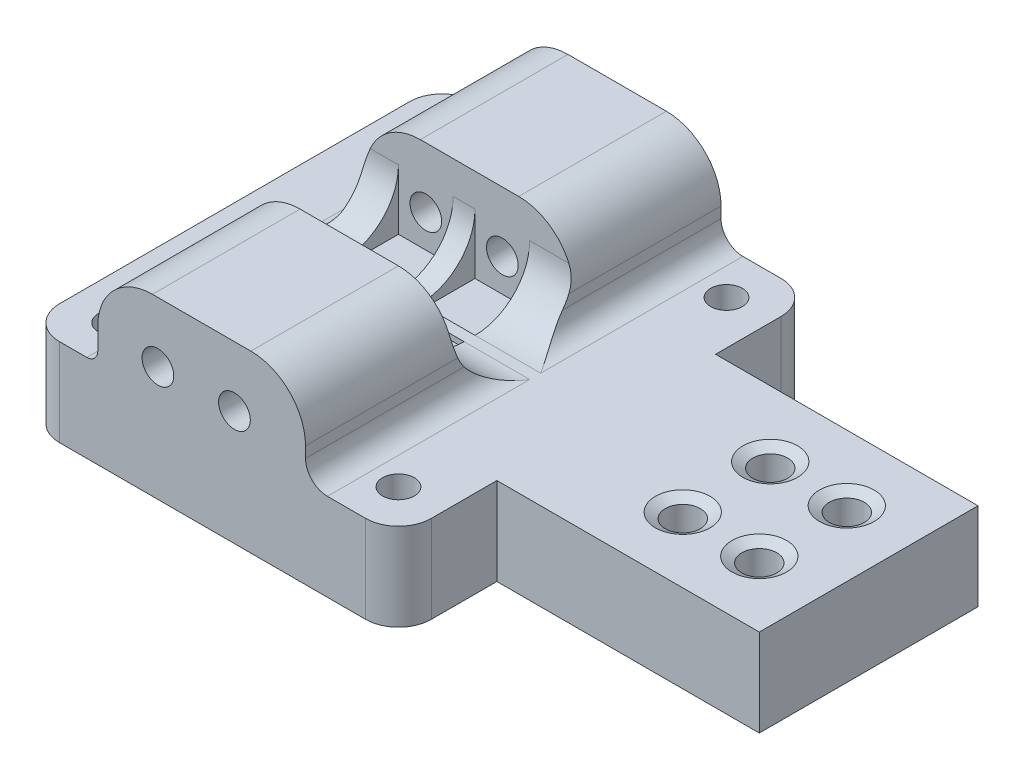
SolidWorks part; units mm, degrees
ref_plane "Front" through (0, 0, 0) normal (0, 0, 1) x (1, 0, 0)
ref_plane "Top" through (0, 0, 0) normal (0, 1, 0) x (1, 0, 0)
ref_plane "Right" through (0, 0, 0) normal (1, 0, 0) x (0, 0, -1)
sketch "Sketch1" plane through (0, 0, 0) normal (0, 1, 0) x (1, 0, 0)
  line L1 (0, 0) -> (300, 0)
  line L2 (0, 0) -> (0, -20)
  line L3 (0, -20) -> (300, -20)
  line L4 (300, 0) -> (300, -20)
  dimension "D1" = 20
  dimension "D2" = 300
extrude "Boss-Extrude1" add sketch "Sketch1" along normal blind 8
sketch "Sketch2" plane through (0, 0, 20) normal (0, 0, 1) x (1, 0, 0)
  line L0 (0, 8) -> (300, 8) construction
  line L1 (0, 0) -> (34, 0)
  line L2 (0, 0) -> (0, 8)
  line L3 (0, 8) -> (34, 8)
  line L4 (34, 0) -> (34, 8)
  line L5 (266, 8) -> (300, 8)
  line L6 (300, 0) -> (300, 8)
  line L7 (266, 0) -> (300, 0)
  line L8 (266, 0) -> (266, 8)
  dimension "D1" = 34
  dimension "D2" = 2
extrude "Boss-Extrude2" add sketch "Sketch2" along normal blind 9
sketch "Sketch3" plane through (0, 0, 0) normal (0, 0, -1) x (-1, 0, 0)
  line L0 (-300, 8) -> (0, 8) construction
  line L1 (0, 0) -> (-34, 0)
  line L2 (0, 0) -> (0, 8)
  line L3 (0, 8) -> (-34, 8)
  line L4 (-34, 0) -> (-34, 8)
  line L5 (-300, 0) -> (-300, 8)
  line L6 (-266, 8) -> (-300, 8)
  line L7 (-266, 0) -> (-266, 8)
  line L8 (-266, 0) -> (-300, 0)
  dimension "D1" = 34
  dimension "D2" = 2
extrude "Boss-Extrude3" add sketch "Sketch3" along normal blind 9
sketch "Sketch4" plane through (0, 8, 0) normal (0, 1, 0) x (1, 0, 0)
  line L0 (0, 9) -> (34, 9) construction
  line L1 (0, 9) -> (0, -29) construction
  circle A0 centre (4, 5) radius 1.45
  circle A1 centre (30, 5) radius 1.45
  circle A2 centre (30, -25) radius 1.45
  circle A3 centre (4, -25) radius 1.45
  circle A4 centre (296, -25) radius 1.45
  circle A5 centre (296, 5) radius 1.45
  circle A6 centre (270, -25) radius 1.45
  circle A7 centre (270, 5) radius 1.45
  dimension "D1" = 2.9
  dimension "D2" = 4
  dimension "D3" = 4
  dimension "D4" = 2
  dimension "D5" = 2
  dimension "D6" = 2
extrude "Cut-Extrude1" cut sketch "Sketch4" against normal through all
sketch "Sketch5" plane through (0, 0, 20) normal (0, 0, 1) x (1, 0, 0)
  line L0 (34, 8) -> (266, 8) construction
  line L1 (266, 0) -> (241, 0)
  line L2 (266, 0) -> (266, 8)
  line L3 (266, 8) -> (241, 8)
  line L4 (241, 0) -> (241, 8)
  dimension "D1" = 25
extrude "Boss-Extrude4" add sketch "Sketch5" along normal blind 17
sketch "Sketch6" plane through (0, 0, 0) normal (0, 0, -1) x (-1, 0, 0)
  line L0 (-266, 0) -> (-34, 0) construction
  line L1 (-266, 8) -> (-241, 8)
  line L2 (-266, 8) -> (-266, 0)
  line L3 (-266, 0) -> (-241, 0)
  line L4 (-241, 8) -> (-241, 0)
  dimension "D1" = 25
extrude "Boss-Extrude5" add sketch "Sketch6" along normal blind 17
sketch "Sketch12" plane through (0, 0, 37) normal (0, 0, 1) x (1, 0, 0)
  line L0 (241, 0) -> (266, 0) construction
  line L1 (241, 8) -> (249, 8)
  line L2 (241, 8) -> (241, 0)
  line L3 (241, 0) -> (249, 0)
  line L4 (249, 8) -> (249, 0)
  dimension "D1" = 8
extrude "Boss-Extrude7" add sketch "Sketch12" along normal blind 17
sketch "Sketch14" plane through (0, 0, 29) normal (0, 0, 1) x (1, 0, 0)
  line L0 (300, 8) -> (266, 8) construction
  line L1 (294.975, 8) -> (275, 8)
  line L2 (294.975, 8) -> (294.975, -5)
  line L3 (294.975, -5) -> (275, -4)
  line L4 (275, 8) -> (275, -4)
  line L7 (266, 8) -> (266, 0) construction
  dimension "D1" = 20
  dimension "D2" = 9
  dimension "D3" = 13
  dimension "D4" = 12
extrude "Boss-Extrude8" add sketch "Sketch14" along normal blind 12
sketch "Sketch15" plane through (294.975, 0, 0) normal (1, 0, 0) x (0, 0, -1)
  line L0 (-41, -5) -> (-41, 8) construction
  line L2 (-41, -5) -> (-29, -5) construction
  circle A0 centre (-35, 0) radius 1.6
  dimension "D1" = 3.2
  dimension "D2" = 6
  dimension "D3" = 5
extrude "Cut-Extrude7" cut sketch "Sketch15" against normal blind 20
sketch "Sketch16" plane through (0, 0, -9) normal (0, 0, -1) x (-1, 0, 0)
  line L0 (-266, 8) -> (-300, 8) construction
  line L1 (-295, 8) -> (-275, 8)
  line L2 (-295, 8) -> (-295, -5)
  line L3 (-295, -5) -> (-275, -5)
  line L4 (-275, 8) -> (-275, -5)
  line L6 (-266, 0) -> (-266, 8) construction
  dimension "D1" = 20
  dimension "D2" = 9
  dimension "D3" = 13
extrude "Boss-Extrude9" add sketch "Sketch16" along normal blind 12
sketch "Sketch17" plane through (295, 0, 0) normal (1, 0, 0) x (0, 0, -1)
  line L0 (21, -5) -> (9, -5) construction
  line L1 (21, 8) -> (21, -5) construction
  circle A0 centre (15, 0) radius 1.6
  dimension "D1" = 3.2
  dimension "D2" = 5
  dimension "D3" = 6
extrude "Cut-Extrude8" cut sketch "Sketch17" against normal blind 20
sketch "Sketch22" plane through (0, 8, 0) normal (0, 1, 0) x (1, 0, 0)
  line L0 (241, 17) -> (241, 0) construction
  line L1 (259, 9) -> (249, 9)
  line L2 (259, 9) -> (259, -29)
  line L3 (259, -29) -> (249, -29)
  line L4 (249, 9) -> (249, -29)
  line L5 (241, 17) -> (266, 17) construction
  line L6 (266, -37) -> (249, -37) construction
  dimension "D1" = 8
  dimension "D2" = 10
  dimension "D3" = 8
  dimension "D4" = 8
extrude "Cut-Extrude11" cut sketch "Sketch22" against normal through all
sketch "Sketch23" plane through (0, 0, 0) normal (0, -1, 0) x (-1, 0, 0)
  line L0 (-259, -29) -> (-259, 9) construction
  line L1 (-259, -19) -> (-267, -19)
  line L2 (-259, -19) -> (-259, -1)
  line L3 (-259, -1) -> (-267, -1)
  line L4 (-267, -19) -> (-267, -1)
  line L5 (-249, -29) -> (-259, -29) construction
  dimension "D1" = 8
  dimension "D2" = 10
  dimension "D3" = 10
extrude "Cut-Extrude12" cut sketch "Sketch23" against normal blind 4
sketch "Sketch24" plane through (259, 0, 0) normal (-1, 0, 0) x (0, 0, 1)
  line L0 (-9, 0) -> (-9, 8)
  line L1 (-9, 8) -> (-1, 8)
  line L2 (29, 8) -> (-9, 8) construction
  line L3 (-1, 8) -> (-9, 0)
  line L4 (29, 0) -> (29, 8)
  line L5 (29, 8) -> (21, 8)
  line L6 (21, 8) -> (29, 0)
  dimension "D1" = 8
  dimension "D2" = 8
extrude "Boss-Extrude12" add sketch "Sketch24" along normal blind 10
sketch "Sketch25" plane through (267, 0, 0) normal (-1, 0, 0) x (0, 0, 1)
  line L0 (19, 0) -> (19, 4)
  line L1 (19, 4) -> (15, 4)
  line L2 (1, 4) -> (19, 4) construction
  line L3 (15, 4) -> (19, 0)
  line L4 (1, 4) -> (5, 4)
  line L5 (5, 4) -> (1, 0)
  line L6 (1, 0) -> (1, 4)
  dimension "D1" = 4
  dimension "D2" = 4
extrude "Boss-Extrude13" add sketch "Sketch25" along normal blind 8
sketch "Sketch26" plane through (0, 8, 0) normal (0, 1, 0) x (1, 0, 0)
  line L0 (249, 1) -> (249, -21) construction
  line L1 (241, -54) -> (249, -54)
  line L2 (241, -54) -> (241, -6)
  line L3 (241, -6) -> (249, -6)
  line L4 (249, -54) -> (249, -6)
  dimension "D1" = 48
extrude "Boss-Extrude14" add sketch "Sketch26" along normal blind 14
sketch "Sketch27" plane through (0, 8, 0) normal (0, 1, 0) x (1, 0, 0)
  line L0 (249, -21) -> (259, -21) construction
  line L1 (249, -37) -> (257, -37)
  line L2 (249, -37) -> (249, -21)
  line L3 (249, -21) -> (257, -21)
  line L4 (257, -37) -> (257, -21)
  dimension "D1" = 8
extrude "Boss-Extrude15" add sketch "Sketch27" along normal blind 14
sketch "Sketch28" plane through (0, 0, 0) normal (0, -1, 0) x (1, 0, 0)
  line L0 (249, -9) -> (249, 29) construction
  line L1 (241, 54) -> (249, 54)
  line L2 (241, 54) -> (241, 14)
  line L3 (241, 14) -> (249, 14)
  line L4 (249, 54) -> (249, 14)
  dimension "D1" = 40
extrude "Cut-Extrude13" cut sketch "Sketch28" against normal blind 14
sketch "Sketch30" plane through (257, 0, 0) normal (1, 0, 0) x (0, 0, -1)
  line L0 (-37, 22) -> (-21, 22) construction
  line L1 (-21, 22) -> (-37, 22)
  line L2 (-21, 22) -> (-21, 8)
  line L3 (-21, 8) -> (-37, 8)
  line L4 (-37, 22) -> (-37, 8)
extrude "Boss-Extrude16" add sketch "Sketch30" along normal blind 9
sketch "Sketch31" plane through (0, 0, 0) normal (0, -1, 0) x (-1, 0, 0)
  line L1 (-249, -37) -> (-266, -37)
  line L2 (-249, -37) -> (-249, -29)
  line L3 (-249, -29) -> (-266, -29)
  line L4 (-266, -37) -> (-266, -29)
extrude "Cut-Extrude14" cut sketch "Sketch31" against normal blind 5
sketch "Sketch32" plane through (266, 0, 0) normal (1, 0, 0) x (0, 0, -1)
  line L0 (-37, 5) -> (-37, 22) construction
  line L1 (-21, 22) -> (-37, 22)
  line L2 (-21, 22) -> (-21, 13)
  line L3 (-21, 13) -> (-37, 13)
  line L4 (-37, 22) -> (-37, 13)
  dimension "D1" = 9
extrude "Cut-Extrude15" cut sketch "Sketch32" against normal blind 9
sketch "Sketch33" plane through (249, 0, 0) normal (-1, 0, 0) x (0, 0, 1)
  line L0 (29, 5) -> (24, 5)
  line L1 (21, 8) -> (29, 0) construction
  line L2 (24, 5) -> (29, 0)
  line L3 (29, 0) -> (29, 5)
extrude "Cut-Extrude16" cut sketch "Sketch33" against normal blind 10
sketch "Sketch34" plane through (0, 0, 29) normal (0, 0, 1) x (1, 0, 0)
  line L1 (266, 5) -> (259, 5)
  line L2 (266, 5) -> (266, 0)
  line L3 (266, 0) -> (259, 0)
  line L4 (259, 5) -> (259, 0)
extrude "Cut-Extrude17" cut sketch "Sketch34" against normal blind 5
sketch "Sketch35" plane through (0, 0, 21) normal (0, 0, -1) x (-1, 0, 0)
  line L0 (-249, 8) -> (-259, 8) construction
  line L1 (-259, 8) -> (-266, 8)
  line L2 (-259, 8) -> (-259, 13)
  line L3 (-259, 13) -> (-266, 13)
  line L4 (-266, 8) -> (-266, 13)
  line L5 (-266, 8) -> (-259, 8) construction
  line L6 (-266, 8) -> (-266, 13) construction
extrude "Boss-Extrude17" add sketch "Sketch35" along normal blind 5
sketch "Sketch36" plane through (0, 22, 0) normal (0, 1, 0) x (1, 0, 0)
  line L0 (241, -54) -> (249, -54) construction
  line L1 (249, -54) -> (249, -37) construction
  circle A0 centre (245, -50) radius 1.7
  circle A1 centre (245, -18) radius 1.7
  dimension "D1" = 3.4
  dimension "D2" = 4
  dimension "D3" = 4
  dimension "D4" = 2
extrude "Cut-Extrude18" cut sketch "Sketch36" against normal through all
sketch "Sketch37" plane through (0, 8, 0) normal (0, 1, 0) x (1, 0, 0)
  line L0 (241, -6) -> (171, -6)
  line L1 (241, -6) -> (241, -14) construction
  line L2 (241, -6) -> (241, -14)
  line L3 (241, -14) -> (241, -20) construction
  line L4 (241, -14) -> (171, -14)
  line L5 (171, -14) -> (171, -6)
  dimension "D1" = 70
extrude "Boss-Extrude18" add sketch "Sketch37" along normal blind 5
sketch "Sketch39" plane through (0, 8, 0) normal (0, 1, 0) x (1, 0, 0)
  line L0 (34, -20) -> (241, -20) construction
  line L1 (241, -14) -> (175, -14)
  line L2 (241, -14) -> (241, -20)
  line L3 (241, -20) -> (175, -20)
  line L4 (175, -14) -> (175, -20)
  dimension "D1" = 66
extrude "Cut-Extrude19" cut sketch "Sketch39" against normal through all
sketch "Sketch46" plane through (0, 8, 0) normal (0, 1, 0) x (1, 0, 0)
  line L1 (295, 9) -> (275, 9)
  line L2 (295, 9) -> (295, 21)
  line L3 (295, 21) -> (275, 21)
  line L4 (275, 9) -> (275, 21)
  line L5 (294.975, -41) -> (275, -41)
  line L6 (294.975, -41) -> (294.975, -29)
  line L7 (294.975, -29) -> (275, -29)
  line L8 (275, -41) -> (275, -29)
extrude "Boss-Extrude23" add sketch "Sketch46" along normal blind 10
sketch "Sketch47" plane through (0, 18, 0) normal (0, 1, 0) x (1, 0, 0)
  line L0 (295, 21) -> (275, 21) construction
  line L1 (275, 21) -> (303, 21)
  line L2 (275, 21) -> (275, 9)
  line L3 (275, 9) -> (303, 9)
  line L4 (303, 21) -> (303, 9)
  line L5 (275, 9) -> (295, 9) construction
  line L6 (294.975, -29) -> (275, -29) construction
  line L7 (274.975, -29) -> (303, -29)
  line L8 (274.975, -29) -> (274.975, -41)
  line L9 (274.975, -41) -> (303, -41)
  line L10 (303, -29) -> (303, -41)
  line L11 (275, -41) -> (294.975, -41) construction
  line L12 (275, 21) -> (275, 9) construction
  line L13 (295, 9) -> (295, 21) construction
  line L14 (275, -29) -> (275, -41) construction
  line L15 (294.975, -41) -> (294.975, -29) construction
  dimension "D1" = 28
  dimension "D2" = 20
  dimension "D3" = 28
  dimension "D4" = 20
extrude "Boss-Extrude24" add sketch "Sketch47" along normal blind 5 and the other way blind 5
sketch "Sketch48" plane through (303, 0, 0) normal (1, 0, 0) x (0, 0, -1)
  line L2 (-41, 13) -> (-41, 23) construction
  line L3 (21, 13) -> (21, 23) construction
  line L4 (9, 23) -> (21, 23) construction
  line L5 (-41, 23) -> (-29, 23) construction
  circle A0 centre (16, 18) radius 1.5
  circle A1 centre (-36, 18) radius 1.5
  dimension "D1" = 3
  dimension "D2" = 3
  dimension "D3" = 5
  dimension "D4" = 5
  dimension "D5" = 5
  dimension "D6" = 5
extrude "Cut-Extrude22" cut sketch "Sketch48" against normal blind 15
sketch "Sketch49" plane through (0, 8, 0) normal (0, 1, 0) x (1, 0, 0)
  line L0 (241, 0) -> (34, 0) construction
  line L1 (34, -20) -> (175, -20) construction
  line L2 (0, 9) -> (0, -29) construction
  circle A0 centre (78, -8) radius 1.45
  circle A1 centre (78, -12) radius 1.45
  dimension "D1" = 2.9
  dimension "D2" = 2.9
  dimension "D3" = 8
  dimension "D4" = 8
  dimension "D5" = 78
  dimension "D6" = 78
extrude "Cut-Extrude23" cut sketch "Sketch49" against normal through all
sketch "Sketch50" plane through (303, 0, 0) normal (1, 0, 0) x (0, 0, -1)
  line L1 (28.7085, 47.789) -> (-67.8332, 47.789)
  line L2 (28.7085, 47.789) -> (28.7085, -51.3705)
  line L3 (28.7085, -51.3705) -> (-67.8332, -51.3705)
  line L4 (-67.8332, 47.789) -> (-67.8332, -51.3705)
extrude "Cut-Extrude24" cut sketch "Sketch50" against normal blind 245
sketch "Sketch51" plane through (0, 8, 0) normal (0, 1, 0) x (1, 0, 0)
  line L1 (34, -20) -> (58, -20) construction
  line L2 (58, 0) -> (34, 0) construction
  line L4 (58, 0) -> (58, -20) construction
  circle A0 centre (52, -14) radius 1.6
  circle A1 centre (45, -14) radius 1.6
  circle A2 centre (45, -6) radius 1.6
  circle A3 centre (52, -6) radius 1.6
  dimension "D1" = 3.2
  dimension "D2" = 3.2
  dimension "D3" = 3.2
  dimension "D4" = 3.2
  dimension "D5" = 6
  dimension "D6" = 6
  dimension "D7" = 6
  dimension "D8" = 6
  dimension "D9" = 7
  dimension "D10" = 7
extrude "Cut-Extrude25" cut sketch "Sketch51" against normal through all
sketch "Sketch52" plane through (0, 8, 0) normal (0, 1, 0) x (1, 0, 0)
  line L0 (0, 9) -> (34, 9) construction
  line L1 (25.5, 9) -> (6.5, 9)
  line L2 (25.5, 9) -> (25.5, -4.5)
  line L3 (25.5, -4.5) -> (6.5, -4.5)
  line L4 (6.5, 9) -> (6.5, -4.5)
  line L5 (34, -29) -> (0, -29) construction
  line L6 (25.5, -29) -> (6.5, -29)
  line L7 (25.5, -29) -> (25.5, -15.5)
  line L8 (25.5, -15.5) -> (6.5, -15.5)
  line L9 (6.5, -29) -> (6.5, -15.5)
  line L10 (0, 9) -> (0, -29) construction
  dimension "D1" = 13.5
  dimension "D2" = 13.5
  dimension "D3" = 19
  dimension "D4" = 19
  dimension "D5" = 6.5
  dimension "D6" = 6.5
extrude "Boss-Extrude25" add sketch "Sketch52" along normal blind 8
fillet "Fillet1" radius 5 2 edges at (16, 8, 4.5) (16, 8, 15.5)
sketch "Sketch53" plane through (0, 0, -9) normal (0, 0, -1) x (-1, 0, 0)
  line L0 (-25.5, 16) -> (-6.5, 16) construction
  line L1 (-6.5, 16) -> (-6.5, 8) construction
  line L2 (-25.5, 16) -> (-25.5, 8) construction
  circle A0 centre (-19, 10.5) radius 1.45
  circle A1 centre (-12, 10.5) radius 1.45
  dimension "D1" = 2.9
  dimension "D2" = 2.9
  dimension "D3" = 5.5
  dimension "D4" = 5.5
  dimension "D5" = 5.5
  dimension "D6" = 6.5
extrude "Cut-Extrude26" cut sketch "Sketch53" against normal through all
fillet "Fillet2" radius 5 4 edges at (25.5, 16, 22.25) (6.5, 16, 22.25) (6.5, 16, -2.25) (25.5, 16, -2.25)
fillet "Fillet3" radius 3 4 edges at (34, 4, 29) (0, 4, 29) (0, 4, -9) (34, 4, -9)
sketch "Sketch54" plane through (0, 16, 0) normal (0, 1, 0) x (1, 0, 0)
  line L0 (11.5, -4.5) -> (20.5, -4.5) construction
  line L1 (16.5, -4.5) -> (21.5, -4.5)
  line L2 (16.5, -4.5) -> (16.5, -9.5)
  line L3 (16.5, -9.5) -> (21.5, -9.5)
  line L4 (21.5, -4.5) -> (21.5, -9.5)
  line L5 (20.5, -15.5) -> (11.5, -15.5) construction
  line L6 (14.5, -4.5) -> (9.5, -4.5)
  line L7 (14.5, -4.5) -> (14.5, -9.5)
  line L8 (14.5, -9.5) -> (9.5, -9.5)
  line L9 (9.5, -4.5) -> (9.5, -9.5)
  line L10 (16.5, -15.5) -> (21.5, -15.5)
  line L11 (16.5, -15.5) -> (16.5, -10.5)
  line L12 (16.5, -10.5) -> (21.5, -10.5)
  line L13 (21.5, -15.5) -> (21.5, -10.5)
  line L14 (11.5, 9) -> (11.5, -4.5) construction
  line L15 (14.5, -15.5) -> (9.5, -15.5)
  line L16 (14.5, -15.5) -> (14.5, -10.5)
  line L17 (14.5, -10.5) -> (9.5, -10.5)
  line L18 (9.5, -15.5) -> (9.5, -10.5)
  line L19 (20.5, -4.5) -> (20.5, 9) construction
  line L20 (11.5, -15.5) -> (11.5, -29) construction
  line L21 (20.5, -29) -> (20.5, -15.5) construction
  dimension "D1" = 5
  dimension "D2" = 5
  dimension "D3" = 5
  dimension "D4" = 5
  dimension "D5" = 3
  dimension "D6" = 4
  dimension "D7" = 5
  dimension "D8" = 5
  dimension "D9" = 5
  dimension "D10" = 5
  dimension "D11" = 3
  dimension "D12" = 4
extrude "Cut-Extrude27" cut sketch "Sketch54" against normal blind 8.5
fillet "Fillet4" radius 1 2 edges at (6.5, 8, 19.75) (6.5, 8, 0.25)
fillet "Fillet5" radius 2 2 edges at (25.5, 8, 19.75) (25.5, 8, 0.25)
sketch "Sketch55" plane through (0, 8, 0) normal (0, 1, 0) x (1, 0, 0)
  circle A0 centre (45, -6) radius 2.5
  circle A1 centre (52, -6) radius 2.5
  circle A2 centre (52, -14) radius 2.5
  circle A3 centre (45, -14) radius 2.5
  dimension "D1" = 5
  dimension "D2" = 5
  dimension "D3" = 5
  dimension "D4" = 5
extrude "Cut-Extrude28" cut sketch "Sketch55" against normal blind 2 draft 60
